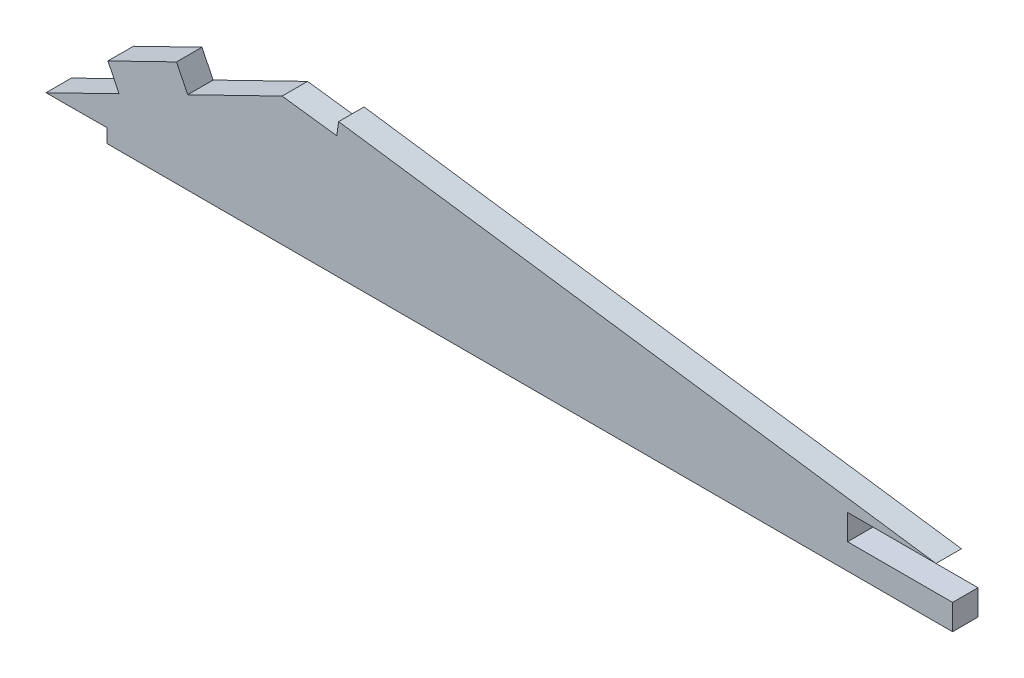
SolidWorks part; units mm, degrees
ref_plane "前视基准面" through (0, 0, 0) normal (0, 0, 1) x (1, 0, 0)
ref_plane "上视基准面" through (0, 0, 0) normal (0, 1, 0) x (1, 0, 0)
ref_plane "右视基准面" through (0, 0, 0) normal (1, 0, 0) x (0, 0, -1)
sketch "Model" plane through (0, 0, 0) normal (0, 0, 1) x (1, 0, 0)
  line L0 (7.756, 7.194) -> (6.8792, 8.9916)
  line L1 (6.8792, 8.9916) -> (12.272, 11.6218)
  line L2 (12.272, 11.6218) -> (13.1488, 9.8242)
  line L3 (7.756, 7.194) -> (2.011, 4.392)
  line L4 (13.1488, 9.8242) -> (20.5726, 13.4451)
  line L5 (6.7967, 3.3274) -> (73.2781, 3.3274)
  line L6 (6.7967, 3.3274) -> (6.7925, 4.4105)
  line L7 (6.7925, 4.4105) -> (2.011, 4.392)
  line L8 (65.0219, 5.3274) -> (73.2781, 5.3274)
  line L9 (65.0219, 7.3274) -> (71.9763, 7.3274)
  line L10 (65.0219, 5.3274) -> (65.0219, 7.3274)
  line L11 (73.2781, 3.3274) -> (73.2781, 5.3274)
  line L12 (25.0151, 13.9273) -> (71.9763, 7.3274)
  line L13 (20.5726, 13.4451) -> (24.8669, 12.8896)
  line L14 (24.8669, 12.8896) -> (25.0151, 13.9273)
  point P16 (25.0151, 13.9317)
extrude "凸台-拉伸1" add sketch "Model" along normal blind 2
